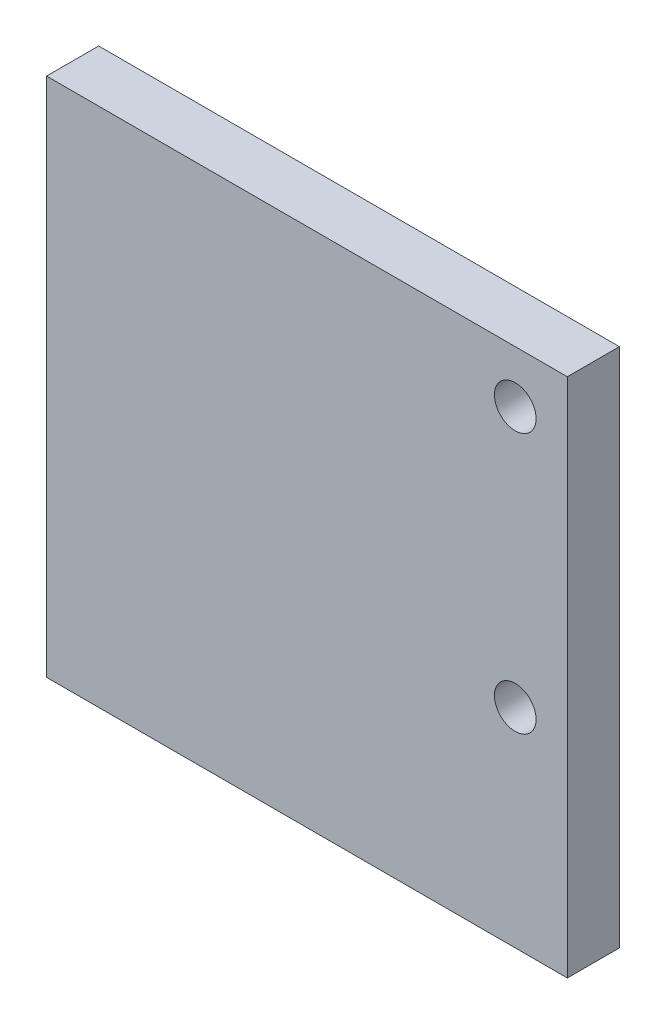
SolidWorks part; units mm, degrees
material "6063-T6"
ref_plane "Front Plane" through (0, 0, 0) normal (0, 0, 1) x (1, 0, 0)
ref_plane "Top Plane" through (0, 0, 0) normal (0, 1, 0) x (1, 0, 0)
ref_plane "Right Plane" through (0, 0, 0) normal (1, 0, 0) x (0, 0, -1)
sketch "Sketch1" plane through (0, 0, 0) normal (0, 0, 1) x (1, 0, 0)
  line L1 (0, 0) -> (100, 0)
  line L2 (0, 0) -> (0, 100)
  line L3 (0, 100) -> (100, 100)
  line L4 (100, 0) -> (100, 100)
  dimension "D1" = 100
  dimension "D2" = 100
extrude "Boss-Extrude1" add sketch "Sketch1" along normal blind 10
sketch "Sketch2" plane through (0, 0, 0) normal (0, -1, 0) x (1, 0, 0)
  line L0 (0, 10) -> (100, 10) construction
  line L1 (100, 10) -> (100, 0) construction
  line L2 (0, 10) -> (0, 0) construction
  circle A0 centre (25, 5) radius 2.5
  circle A1 centre (50, 5) radius 2.5
  circle A2 centre (75, 5) radius 2.5
  dimension "D1" = 5
  dimension "D2" = 5
  dimension "D3" = 5
  dimension "D4" = 5
  dimension "D5" = 5
  dimension "D6" = 25
  dimension "D7" = 5
  dimension "D8" = 50
  dimension "D9" = 25
extrude "Cut-Extrude1" cut sketch "Sketch2" against normal blind 30
sketch "Sketch3" plane through (0, 0, 10) normal (0, 0, 1) x (1, 0, 0)
  line L0 (100, 100) -> (0, 100) construction
  line L1 (100, 0) -> (100, 100) construction
  line L2 (0, 0) -> (100, 0) construction
  circle A0 centre (90, 90) radius 4
  circle A1 centre (90, 40) radius 4
  dimension "D1" = 8
  dimension "D2" = 10
  dimension "D3" = 10
  dimension "D4" = 8
  dimension "D5" = 10
  dimension "D6" = 40
extrude "Cut-Extrude2" cut sketch "Sketch3" against normal blind 10
